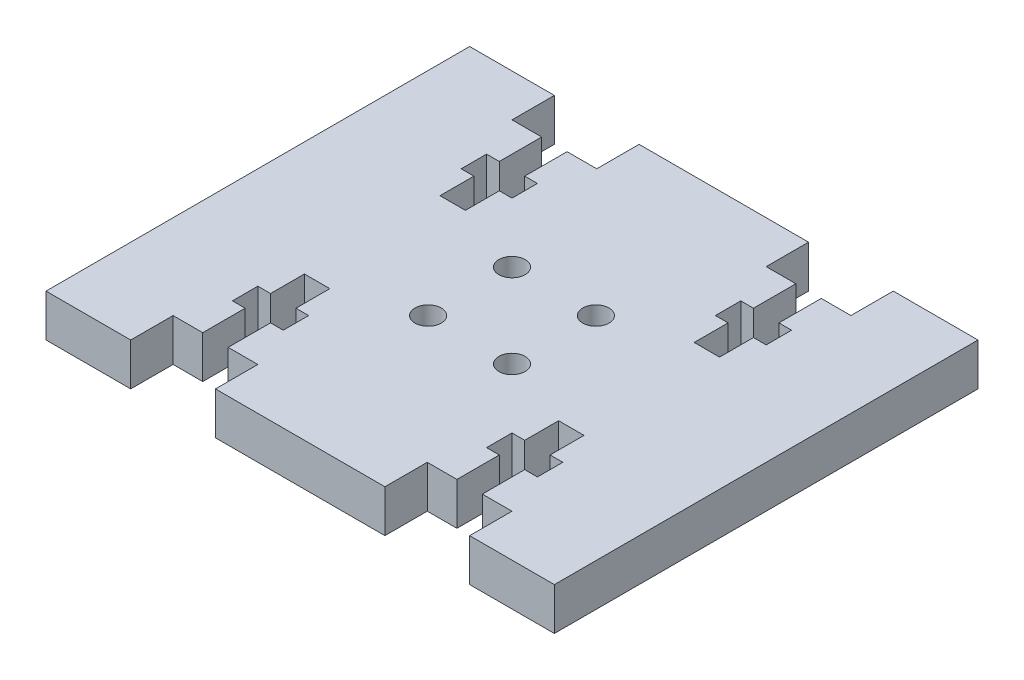
SolidWorks part; units mm, degrees
ref_plane "Front Plane" through (0, 0, 0) normal (0, 0, 1) x (1, 0, 0)
ref_plane "Top Plane" through (0, 0, 0) normal (0, 1, 0) x (1, 0, 0)
ref_plane "Right Plane" through (0, 0, 0) normal (1, 0, 0) x (0, 0, -1)
sketch "Sketch1" plane through (0, 0, 0) normal (0, 1, 0) x (1, 0, 0)
  line L0 (0, 5.541) -> (0, 0) construction
  line L1 (0, 0) -> (-6.4168, 0) construction
  line L2 (0, 5.541) -> (0, 29.3529) construction
  line L3 (-30, 20) -> (30, 20)
  line L4 (-30, 20) -> (-30, -20)
  line L5 (-30, -20) -> (30, -20)
  line L6 (30, 20) -> (30, -20)
  line L7 (-30, 20) -> (30, -20) construction
  line L8 (-30, -20) -> (30, 20) construction
  line L9 (-30, 20) -> (-20, 20)
  line L10 (-30, 20) -> (-30, 25)
  line L11 (-30, 25) -> (-20, 25)
  line L12 (-20, 20) -> (-20, 25)
  line L13 (10, 25) -> (-10, 25)
  line L14 (-10, 25) -> (-10, 20)
  line L15 (10, 25) -> (10, 20)
  line L16 (20, 20) -> (20, 25)
  line L17 (30, 25) -> (20, 25)
  line L18 (30, 20) -> (30, 25)
  line L19 (30, -20) -> (30, -25)
  line L20 (30, -25) -> (20, -25)
  line L21 (20, -20) -> (20, -25)
  line L22 (10, -25) -> (10, -20)
  line L23 (10, -25) -> (-10, -25)
  line L24 (-10, -25) -> (-10, -20)
  line L25 (-20, -20) -> (-20, -25)
  line L26 (-30, -25) -> (-20, -25)
  line L27 (-30, -20) -> (-30, -25)
  line L28 (-15, 8) -> (-15, 20) construction
  line L29 (-16.5, 20) -> (-13.5, 20)
  line L30 (-16.5, 20) -> (-16.5, 8)
  line L31 (-16.5, 8) -> (-13.5, 8)
  line L32 (-13.5, 20) -> (-13.5, 8)
  line L33 (16.5, 8) -> (13.5, 8)
  line L34 (-18, 15) -> (-12, 15)
  line L35 (-18, 15) -> (-18, 12)
  line L36 (-18, 12) -> (-12, 12)
  line L37 (-12, 15) -> (-12, 12)
  line L38 (-18, 15) -> (-12, 12) construction
  line L39 (-18, 12) -> (-12, 15) construction
  line L40 (18, 12) -> (12, 12)
  line L41 (12, 15) -> (12, 12)
  line L42 (13.5, 20) -> (13.5, 8)
  line L43 (18, 15) -> (18, 12)
  line L44 (18, 15) -> (12, 15)
  line L45 (16.5, 20) -> (16.5, 8)
  line L46 (16.5, -8) -> (13.5, -8)
  line L47 (18, -12) -> (12, -12)
  line L48 (12, -15) -> (12, -12)
  line L49 (18, -15) -> (18, -12)
  line L50 (18, -15) -> (12, -15)
  line L51 (16.5, -20) -> (16.5, -8)
  line L52 (13.5, -20) -> (13.5, -8)
  line L53 (-16.5, -8) -> (-13.5, -8)
  line L54 (-18, -12) -> (-12, -12)
  line L55 (-18, -15) -> (-18, -12)
  line L56 (-12, -15) -> (-12, -12)
  line L57 (-13.5, -20) -> (-13.5, -8)
  line L58 (-16.5, -20) -> (-16.5, -8)
  line L59 (-18, -15) -> (-12, -15)
  circle A0 centre (-4.95, 4.95) radius 1.55
  circle A1 centre (-4.95, -4.95) radius 1.55
  circle A2 centre (4.95, -4.95) radius 1.55
  circle A3 centre (4.95, 4.95) radius 1.55
  point P24 (0, 25)
  point P44 (-15, 13.5)
  dimension "D1" = 3.1
  dimension "D2" = 4.95
  dimension "D3" = 4.95
  dimension "D4" = 40
  dimension "D5" = 60
  dimension "D6" = 5
  dimension "D7" = 10
  dimension "D8" = 10
  dimension "D9" = 3
  dimension "D10" = 5
  dimension "D11" = 12
  dimension "D12" = 5
  dimension "D13" = 6
  dimension "D14" = 3
extrude "Boss-Extrude1" add sketch "Sketch1" along normal blind 5 contours L59 L55 L54 L58 L53 L57 L56 L5 L52 L50 L48 L47 L46 L51 L49 L6 L3 L45 L44 L43 L40 L33 L42 L41 L32 L34 L37 L36 L31 L30 | L24 L23 L22 L5 | L5 L21 L20 L19 | L5 L27 L26 L25 | L3 L18 L17 L16 | L15 L13 L14 L3 | L3 L12 L11 L10
